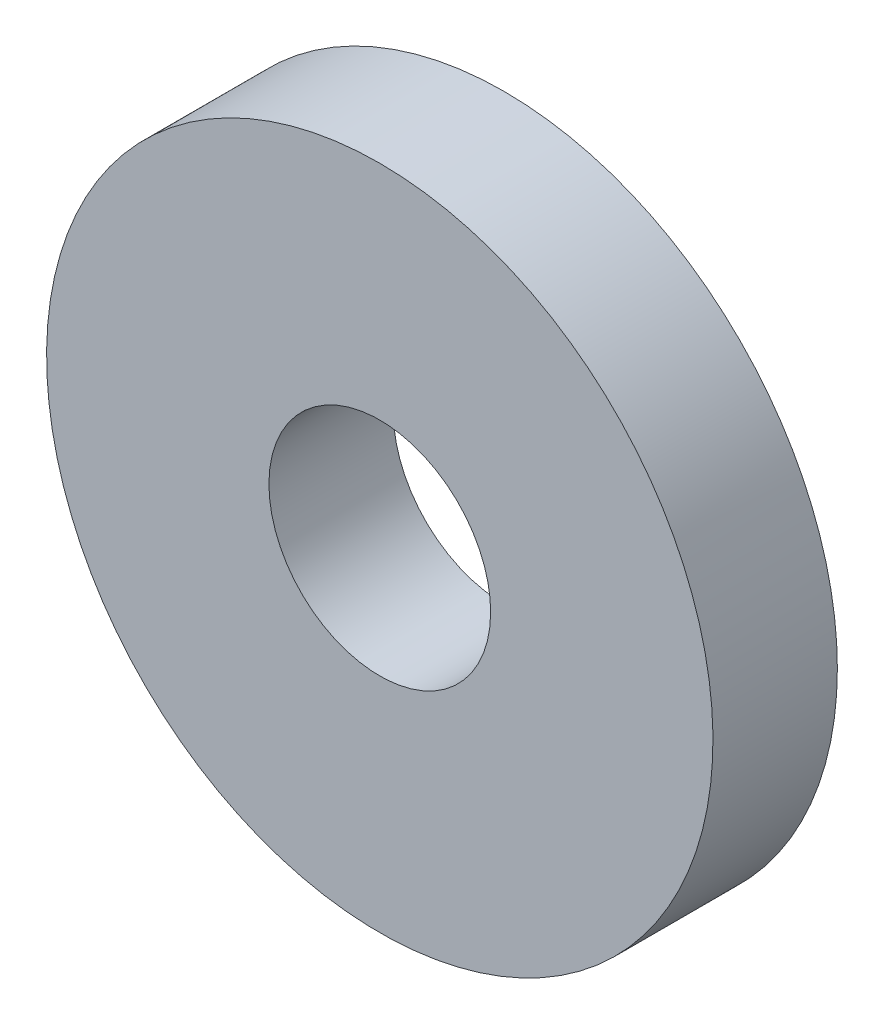
SolidWorks part; units mm, degrees
ref_plane "Front Plane" through (0, 0, 0) normal (0, 0, 1) x (1, 0, 0)
ref_plane "Top Plane" through (0, 0, 0) normal (0, 1, 0) x (1, 0, 0)
ref_plane "Right Plane" through (0, 0, 0) normal (1, 0, 0) x (0, 0, -1)
sketch "Sketch1" plane through (0, 0, 0) normal (0, 0, 1) x (1, 0, 0)
  circle A0 centre (0, 0) radius 7.5
  circle A1 centre (0, 0) radius 2.4955
  circle A2 centre (0, 0) radius 7.5 construction
  circle A3 centre (0, 0) radius 2.4955 construction
extrude "Boss-Extrude1" add sketch "Sketch1" along normal up to surface (2.8 mm away) contours A0 A1
